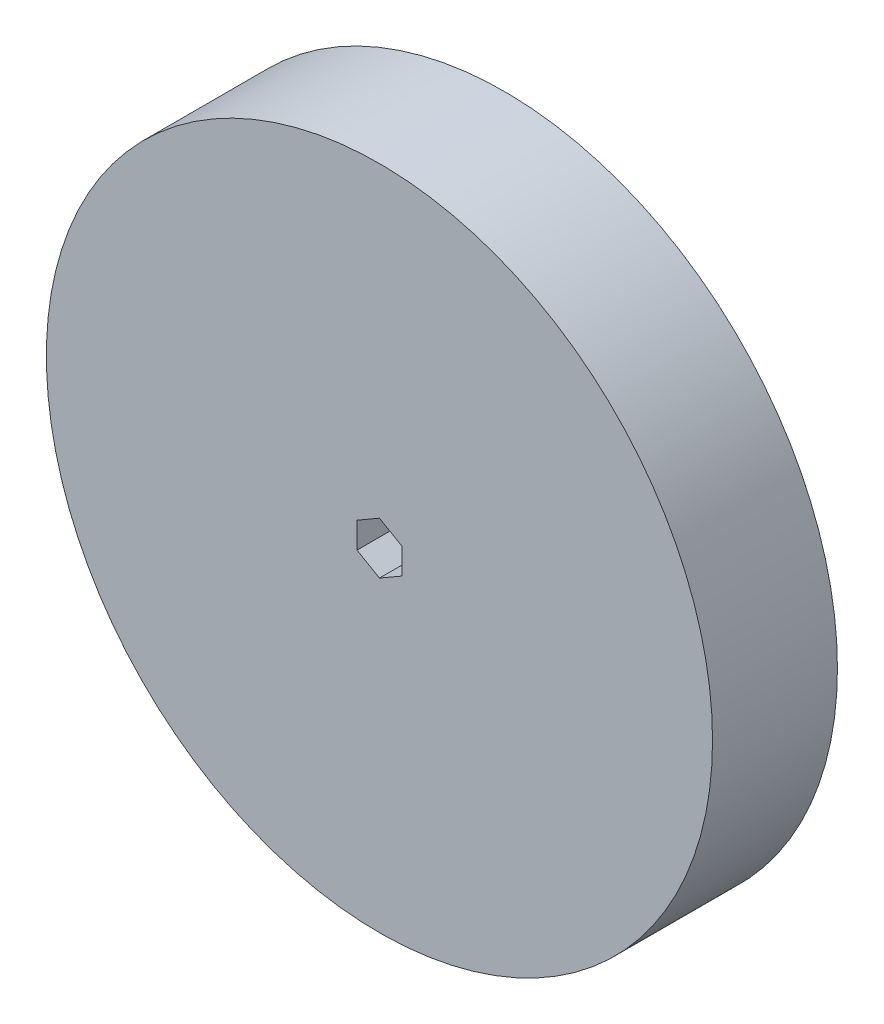
SolidWorks part; units mm, degrees
ref_plane "Front Plane" through (0, 0, 0) normal (0, 0, 1) x (1, 0, 0)
ref_plane "Top Plane" through (0, 0, 0) normal (0, 1, 0) x (1, 0, 0)
ref_plane "Right Plane" through (0, 0, 0) normal (1, 0, 0) x (0, 0, -1)
sketch "Sketch1" plane through (0, 0, 0) normal (0, 0, 1) x (1, 0, 0)
  line L1 (0, 7.9097) -> (-6.85, 3.9548)
  line L2 (-6.85, 3.9548) -> (-6.85, -3.9548)
  line L3 (-6.85, -3.9548) -> (0, -7.9097)
  line L4 (0, -7.9097) -> (6.85, -3.9548)
  line L5 (6.85, -3.9548) -> (6.85, 3.9548)
  line L6 (6.85, 3.9548) -> (0, 7.9097)
  circle A0 centre (0, 0) radius 6.85 construction
  circle A1 centre (0, 0) radius 101.6
  dimension "D1" = 13.7
  dimension "D2" = 203.2
extrude "Boss-Extrude1" add sketch "Sketch1" against normal blind 38.1
sketch "Sketch2" plane through (0, 0, 0) normal (1, 0, 0) x (0, 0, -1)
  line L0 (0, 101.6) -> (0, -101.6) construction
  line L1 (0, 101.6) -> (0, -101.6) construction
  line L2 (0, 101.6) -> (2.9611, 95.25)
  line L3 (2.9611, 95.25) -> (35.1389, 95.25)
  line L4 (35.1389, 95.25) -> (38.1, 101.6)
  line L5 (38.1, -101.6) -> (38.1, 101.6) construction
  line L6 (0, 101.6) -> (38.1, 101.6)
  point P8 (0, 0)
  point P10 (0, 0)
  dimension "D1" = 25
  dimension "D2" = 25
  dimension "D3" = 6.35
